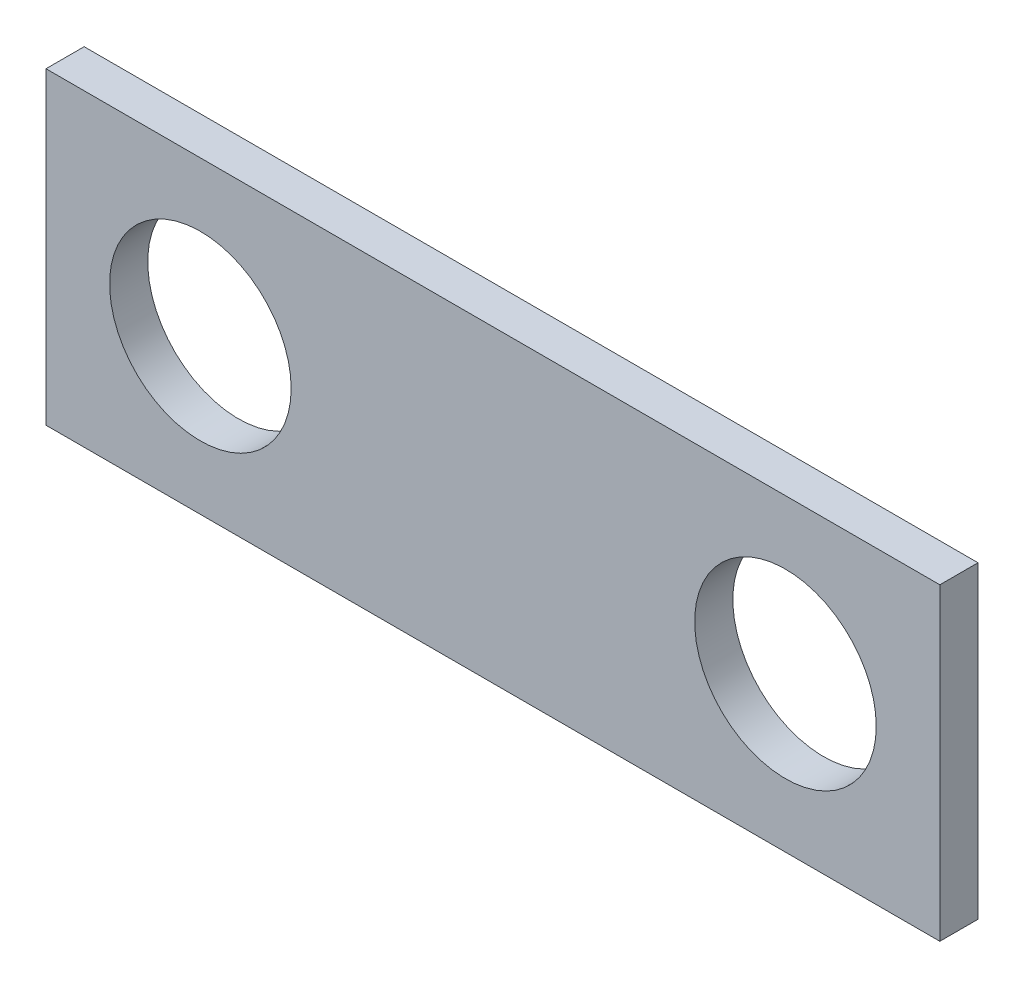
SolidWorks part; units mm, degrees
ref_plane "Front Plane" through (0, 0, 0) normal (0, 0, 1) x (1, 0, 0)
ref_plane "Top Plane" through (0, 0, 0) normal (0, 1, 0) x (1, 0, 0)
ref_plane "Right Plane" through (0, 0, 0) normal (1, 0, 0) x (0, 0, -1)
sketch "Sketch1" plane through (0, 0, 0) normal (0, 0, 1) x (1, 0, 0)
  line L0 (10, 48.5496) -> (10, 0) construction
  line L1 (0, 0) -> (140.5496, 0)
  line L2 (0, 0) -> (0, 48.5496)
  line L3 (0, 48.5496) -> (140.5496, 48.5496)
  line L4 (140.5496, 0) -> (140.5496, 48.5496)
  line L5 (130.5496, 48.5496) -> (130.5496, 0) construction
  line L6 (0, 10) -> (140.5496, 10) construction
  line L7 (0, 38.5496) -> (140.5496, 38.5496) construction
  circle A0 centre (24.2748, 24.2748) radius 14.2748
  circle A1 centre (116.2748, 24.2748) radius 14.2748
  dimension "D5" = 28.5496
  dimension "D1" = 10
  dimension "D2" = 10
  dimension "D3" = 10
  dimension "D4" = 10
  dimension "D6" = 92
extrude "Boss-Extrude1" add sketch "Sketch1" along normal blind 6
